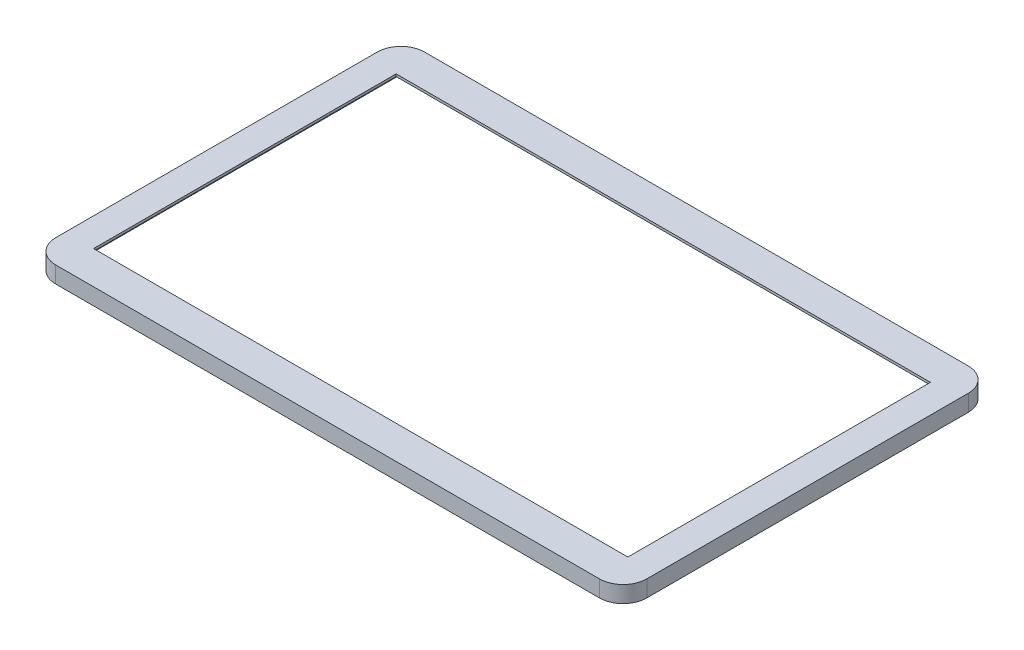
SolidWorks part; units mm, degrees
ref_plane "前视基准面" through (0, 0, 0) normal (0, 0, 1) x (1, 0, 0)
ref_plane "上视基准面" through (0, 0, 0) normal (0, 1, 0) x (1, 0, 0)
ref_plane "右视基准面" through (0, 0, 0) normal (1, 0, 0) x (0, 0, -1)
sketch "草图1" plane through (0, 0, 0) normal (0, 1, 0) x (1, 0, 0)
  line L1 (-99.3407, 63.102) -> (150.6593, 63.102)
  line L2 (-99.3407, 63.102) -> (-99.3407, -92.898)
  line L3 (-99.3407, -92.898) -> (150.6593, -92.898)
  line L4 (150.6593, 63.102) -> (150.6593, -92.898)
  line L5 (-87.3407, 49.102) -> (138.6593, 49.102)
  line L6 (-87.3407, 49.102) -> (-87.3407, -78.898)
  line L7 (-90.3407, 52.102) -> (143.6593, 52.102) construction
  line L8 (-90.3407, 52.102) -> (-90.3407, -85.898) construction
  line L9 (-90.3407, -85.898) -> (143.6593, -85.898) construction
  line L10 (143.6593, 52.102) -> (143.6593, -85.898) construction
  line L11 (-87.3407, -78.898) -> (138.6593, -78.898)
  line L12 (138.6593, 49.102) -> (138.6593, -78.898)
  point P4 (18.2503, -8.9096)
  point P9 (19.2503, -5.5256)
  point P14 (25.6593, -14.898)
  dimension "D1" = 250
  dimension "D2" = 156
  dimension "D3" = 138
  dimension "D4" = 234
  dimension "D5" = 9
  dimension "D6" = 7
  dimension "D7" = 11
  dimension "D8" = 7
  dimension "D9" = 3
  dimension "D10" = 3
  dimension "D11" = 7
  dimension "D12" = 5
extrude "凸台-拉伸1" add sketch "草图1" along normal blind 8
sketch "草图2" plane through (0, 0, 0) normal (0, -1, 0) x (1, 0, 0)
  line L0 (-99.3407, -63.102) -> (-99.3407, 92.898) construction
  line L1 (-93.0907, 82.648) -> (142.4093, 82.648)
  line L2 (-93.0907, 82.648) -> (-93.0907, -56.852)
  line L3 (-93.0907, -56.852) -> (142.4093, -56.852)
  line L4 (142.4093, 82.648) -> (142.4093, -56.852)
  line L5 (-93.0907, 82.648) -> (142.4093, -56.852) construction
  line L6 (-93.0907, -56.852) -> (142.4093, 82.648) construction
  line L7 (-99.3407, 92.898) -> (150.6593, 92.898) construction
  line L13 (150.6593, 92.898) -> (150.6593, -63.102) construction
  line L14 (150.6593, -63.102) -> (-99.3407, -63.102) construction
  point P4 (24.6593, 12.898)
  dimension "D1" = 235.5
  dimension "D2" = 139.5
  dimension "D3" = 6.25
  dimension "D4" = 10.25
  dimension "D5" = 8.25
  dimension "D6" = 6.25
extrude "切除-拉伸3" cut sketch "草图2" against normal blind 6
sketch "草图3" plane through (0, 8, 0) normal (0, 1, 0) x (1, 0, 0)
  line L0 (-89.3407, 63.102) -> (-99.3407, 63.102)
  line L2 (-99.3407, 63.102) -> (-99.3407, 53.102)
  arc A0 (-99.3407, 53.102) -> (-89.3407, 63.102) centre (-89.3407, 53.102) cw
  point P10 (-99.3407, 63.102)
  dimension "D1" = 10
extrude "切除-拉伸4" cut sketch "草图3" against normal blind 10
sketch "草图4" plane through (0, 8, 0) normal (0, 1, 0) x (1, 0, 0)
  line L0 (-99.3407, -82.898) -> (-99.3407, -92.898)
  line L2 (-99.3407, -92.898) -> (-89.3407, -92.898)
  line L4 (150.6593, -82.898) -> (150.6593, -92.898)
  line L6 (150.6593, -92.898) -> (140.6593, -92.898)
  line L8 (140.6593, 63.102) -> (150.6593, 63.102)
  line L10 (150.6593, 63.102) -> (150.6593, 53.102)
  arc A0 (-99.3407, -82.898) -> (-89.3407, -92.898) centre (-89.3407, -82.898) ccw
  arc A1 (140.6593, -92.898) -> (150.6593, -82.898) centre (140.6593, -82.898) ccw
  arc A2 (150.6593, 53.102) -> (140.6593, 63.102) centre (140.6593, 53.102) ccw
  point P10 (-99.3407, -92.898)
  point P16 (150.6593, -92.898)
  point P22 (150.6593, 63.102)
  dimension "D1" = 10
  dimension "D2" = 10
  dimension "D3" = 10
extrude "切除-拉伸5" cut sketch "草图4" against normal blind 10
sketch "草图6" plane through (0, 8, 0) normal (0, 1, 0) x (1, 0, 0)
  line L0 (-99.3407, 53.102) -> (-99.3407, -82.898) construction
  line L1 (-99.3407, 63.102) -> (150.6593, 63.102)
  line L2 (-99.3407, 63.102) -> (-99.3407, -92.898)
  line L3 (-99.3407, -92.898) -> (150.6593, -92.898)
  line L4 (150.6593, 63.102) -> (150.6593, -92.898)
  line L5 (-99.3407, 63.102) -> (150.6593, -92.898) construction
  line L6 (-99.3407, -92.898) -> (150.6593, 63.102) construction
  line L7 (140.6593, 63.102) -> (-89.3407, 63.102) construction
  line L8 (150.6593, -82.898) -> (150.6593, 53.102) construction
  line L9 (-89.3407, -92.898) -> (140.6593, -92.898) construction
  point P4 (25.6593, -14.898)
extrude "切除-拉伸6" cut sketch "草图6" against normal blind 1
